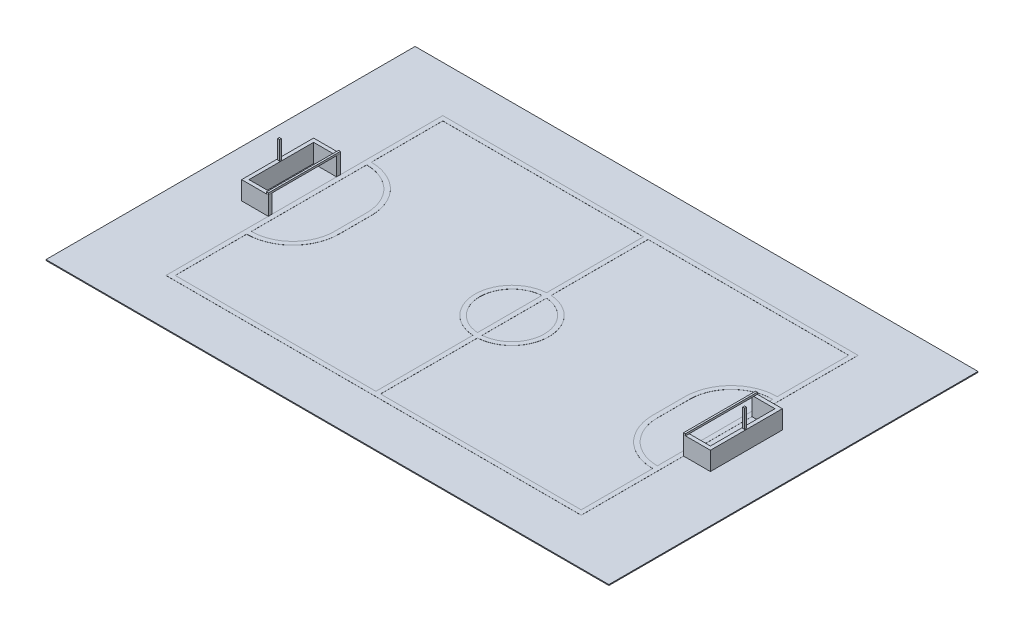
SolidWorks part; units mm, degrees
ref_plane "Front Plane" through (0, 0, 0) normal (0, 0, 1) x (1, 0, 0)
ref_plane "Top Plane" through (0, 0, 0) normal (0, 1, 0) x (1, 0, 0)
ref_plane "Right Plane" through (0, 0, 0) normal (1, 0, 0) x (0, 0, -1)
sketch "Sketch1" plane through (0, 0, 0) normal (0, 1, 0) x (1, 0, 0)
  line L1 (0, 0) -> (6100, 0)
  line L2 (0, 0) -> (0, 4000)
  line L3 (0, 4000) -> (6100, 4000)
  line L4 (6100, 0) -> (6100, 4000)
  dimension "D1" = 6100
  dimension "D2" = 4000
extrude "Boss-Extrude1" add sketch "Sketch1" along normal blind 10
sketch "Sketch4" plane through (0, 10, 0) normal (0, 1, 0) x (1, 0, 0)
  line L0 (850, 2675) -> (850, 3450)
  line L1 (800, 3500) -> (5300, 3500)
  line L2 (800, 3500) -> (800, 500)
  line L3 (800, 500) -> (5300, 500)
  line L4 (5300, 3500) -> (5300, 500)
  line L5 (850, 3450) -> (3025, 3450)
  line L6 (3025, 3450) -> (3025, 2399.218)
  line L7 (3075, 2399.218) -> (3075, 3450)
  line L8 (3075, 3450) -> (5250, 3450)
  line L9 (5250, 3450) -> (5250, 2675)
  line L10 (5250, 1325) -> (5250, 550)
  line L11 (5250, 550) -> (3075, 550)
  line L12 (3075, 550) -> (3075, 1600.782)
  line L13 (3025, 1600.782) -> (3025, 550)
  line L14 (3025, 550) -> (850, 550)
  line L15 (850, 550) -> (850, 1325)
  line L16 (1350, 2175) -> (1350, 1825)
  line L17 (4750, 2175) -> (4750, 1825)
  line L18 (3025, 2349.106) -> (3025, 1650.894)
  line L19 (3075, 2349.106) -> (3075, 1650.894)
  line L20 (5250, 2625) -> (5250, 1375)
  line L21 (4800, 2175) -> (4800, 1825)
  line L22 (850, 2625) -> (850, 1375)
  line L23 (1300, 2175) -> (1300, 1825)
  line L26 (0, 0) -> (6100, 0) construction
  line L27 (0, 4000) -> (0, 0) construction
  arc A0 (850, 2675) -> (1350, 2175) centre (850, 2175) cw
  arc A1 (850, 1325) -> (1350, 1825) centre (850, 1825) ccw
  arc A2 (5250, 2675) -> (4750, 2175) centre (5250, 2175) ccw
  arc A3 (5250, 1325) -> (4750, 1825) centre (5250, 1825) cw
  arc A4 (3025, 2399.218) -> (3025, 1600.782) centre (3050, 2000) ccw
  arc A5 (3075, 2399.218) -> (3075, 1600.782) centre (3050, 2000) cw
  arc A6 (3025, 2349.106) -> (3025, 1650.894) centre (3050, 2000) ccw
  arc A7 (3075, 2349.106) -> (3075, 1650.894) centre (3050, 2000) cw
  arc A8 (5250, 2625) -> (4800, 2175) centre (5250, 2175) ccw
  arc A9 (5250, 1375) -> (4800, 1825) centre (5250, 1825) cw
  arc A10 (850, 2625) -> (1300, 2175) centre (850, 2175) cw
  arc A11 (850, 1375) -> (1300, 1825) centre (850, 1825) ccw
  dimension "D11" = 400
  dimension "D13" = 50
  dimension "D14" = 50
  dimension "D15" = 1500
  dimension "D17" = 500
  dimension "D20" = 500
  dimension "D1" = 3000
  dimension "D2" = 4500
  dimension "D3" = 500
  dimension "D4" = 800
  dimension "D5" = 50
  dimension "D6" = 50
  dimension "D7" = 50
  dimension "D8" = 50
  dimension "D9" = 2175
  dimension "D10" = 50
  dimension "D12" = 50
  dimension "D16" = 50
  dimension "D18" = 350
  dimension "D19" = 1325
  dimension "D21" = 50
  dimension "D22" = 350
  dimension "D23" = 1325
extrude "Boss-Extrude3" add sketch "Sketch4" along normal blind 1
sketch "Sketch5" plane through (0, 10, 0) normal (0, 1, 0) x (1, 0, 0)
  line L10 (5300, 2390) -> (5590, 2390)
  line L11 (5300, 500) -> (5300, 3500) construction
  line L12 (5590, 2390) -> (5590, 1610)
  line L13 (5590, 1610) -> (5300, 1610)
  line L14 (5300, 1610) -> (5300, 1650)
  line L15 (5300, 500) -> (5300, 3500) construction
  line L16 (5300, 1650) -> (5550, 1650)
  line L17 (5550, 1650) -> (5550, 2350)
  line L18 (5550, 2350) -> (5300, 2350)
  line L19 (5300, 2350) -> (5300, 2390)
  dimension "D7" = 250
  dimension "D8" = 700
  dimension "D9" = 40
  dimension "D10" = 40
  dimension "D11" = 40
  dimension "D12" = 175
extrude "Boss-Extrude4" add sketch "Sketch5" along normal blind 200
sketch "Sketch9" plane through (0, 10, 0) normal (0, 1, 0) x (1, 0, 0)
  line L0 (800, 2390) -> (800, 2350)
  line L1 (800, 3500) -> (800, 500) construction
  line L2 (800, 3500) -> (800, 500) construction
  line L3 (800, 2350) -> (550, 2350)
  line L4 (550, 2350) -> (550, 1650)
  line L5 (550, 1650) -> (800, 1650)
  line L6 (800, 1650) -> (800, 1610)
  line L7 (800, 1610) -> (510, 1610)
  line L8 (510, 1610) -> (510, 2390)
  line L9 (510, 2390) -> (800, 2390)
  dimension "D1" = 250
  dimension "D2" = 40
  dimension "D3" = 700
  dimension "D4" = 40
  dimension "D5" = 40
  dimension "D6" = 175
extrude "Boss-Extrude8" add sketch "Sketch9" along normal blind 200 separate body
sketch "Sketch10" plane through (0, 210, 0) normal (0, 1, 0) x (1, 0, 0)
  line L0 (550, 2350) -> (800, 2350) construction
  line L1 (520, 2010) -> (540, 2010)
  line L2 (520, 2010) -> (520, 1990)
  line L3 (520, 1990) -> (540, 1990)
  line L4 (540, 2010) -> (540, 1990)
  line L5 (510, 2390) -> (510, 1610) construction
  line L6 (5590, 1610) -> (5590, 2390) construction
  line L7 (5560, 2010) -> (5580, 2010)
  line L8 (5560, 2010) -> (5560, 1990)
  line L9 (5560, 1990) -> (5580, 1990)
  line L10 (5580, 2010) -> (5580, 1990)
  line L11 (5300, 2350) -> (5550, 2350) construction
  dimension "D1" = 340
  dimension "D2" = 20
  dimension "D3" = 20
  dimension "D4" = 10
  dimension "D5" = 10
  dimension "D6" = 20
  dimension "D7" = 20
  dimension "D8" = 340
extrude "Boss-Extrude9" add sketch "Sketch10" along normal blind 200 separate body
sketch "Sketch11" plane through (0, 0, -1610) normal (0, 0, 1) x (1, 0, 0)
  line L1 (800, 210) -> (780, 210)
  line L2 (800, 210) -> (800, 230)
  line L3 (800, 230) -> (780, 230)
  line L4 (780, 210) -> (780, 230)
  line L5 (5300, 210) -> (5320, 210)
  line L6 (5300, 210) -> (5300, 230)
  line L7 (5300, 230) -> (5320, 230)
  line L8 (5320, 210) -> (5320, 230)
  dimension "D1" = 20
  dimension "D2" = 20
  dimension "D3" = 20
  dimension "D4" = 20
extrude "Boss-Extrude10" add sketch "Sketch11" against normal up to surface (780 mm away) separate body up to face at (655, 110, -2390)
